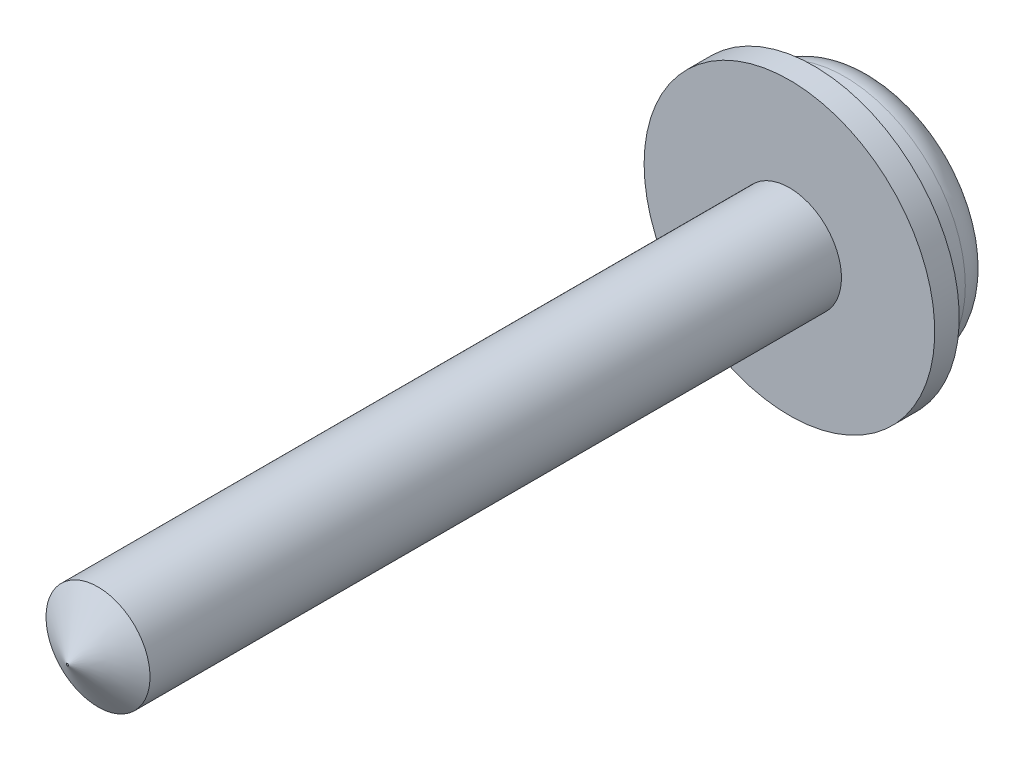
SolidWorks part; units mm, degrees
ref_plane "Plano frontal" through (0, 0, 0) normal (0, 0, 1) x (1, 0, 0)
ref_plane "Plano superior" through (0, 0, 0) normal (0, 1, 0) x (1, 0, 0)
ref_plane "Plano direito" through (0, 0, 0) normal (1, 0, 0) x (0, 0, -1)
sketch "Esboço1" plane through (0, 0, 0) normal (0, 0, 1) x (1, 0, 0)
  circle A0 centre (0, 0) radius 0.85
  dimension "D1" = 1.7
extrude "Ressalto-extrusão1" add sketch "Esboço1" along normal blind 11.8
chamfer "Chanfro1" distance 0.5 angle 59 1 edges at (0.85, 0, 11.8)
sketch "Esboço2" plane through (0, 0, 0) normal (0, 0, -1) x (-1, 0, 0)
  circle A0 centre (0, 0) radius 2.375
  dimension "D1" = 4.75
extrude "Ressalto-extrusão2" add sketch "Esboço2" along normal blind 0.4
sketch "Esboço3" plane through (0, 0, -0.4) normal (0, 0, -1) x (-1, 0, 0)
  circle A0 centre (0, 0) radius 1.975
  circle A1 centre (0, 0) radius 2.375 construction
  dimension "D1" = 0.4
extrude "Ressalto-extrusão3" add sketch "Esboço3" along normal blind 1
fillet "Filete1" radius 0.5 1 edges at (-1.975, 0, -1.4)
sketch "Esboço4" plane through (0, 0, -1.4) normal (0, 0, -1) x (-1, 0, 0)
  line L0 (-0.6, 0.3) -> (-1.15, 0.3)
  line L1 (0.3, -1.15) -> (-0.3, -1.15)
  line L2 (0.3, -1.15) -> (0.3, -0.6)
  line L3 (0.3, 1.15) -> (-0.3, 1.15)
  line L4 (-0.3, -1.15) -> (-0.3, -0.6)
  line L7 (1.15, -0.3) -> (0.6, -0.3)
  line L8 (1.15, -0.3) -> (1.15, 0.3)
  line L9 (1.15, 0.3) -> (0.6, 0.3)
  line L10 (-1.15, -0.3) -> (-1.15, 0.3)
  line L13 (0.3, 0.6) -> (0.3, 1.15)
  line L16 (-0.6, -0.3) -> (-1.15, -0.3)
  line L18 (-0.3, 0.6) -> (-0.3, 1.15)
  arc A0 (0.3, -0.6) -> (0.6, -0.3) centre (0.6, -0.6) cw
  arc A1 (0.3, 0.6) -> (0.6, 0.3) centre (0.6, 0.6) ccw
  arc A2 (-0.6, 0.3) -> (-0.3, 0.6) centre (-0.6, 0.6) ccw
  arc A3 (-0.6, -0.3) -> (-0.3, -0.6) centre (-0.6, -0.6) cw
  point P0 (0, 0)
  point P6 (0, 0)
  point P22 (-0.3, 0.3)
  dimension "D5" = 0.3
  dimension "D1" = 0.6
  dimension "D2" = 2.3
  dimension "D3" = 0.6
  dimension "D4" = 2.3
extrude "Corte-extrusão1" cut sketch "Esboço4" against normal blind 1
